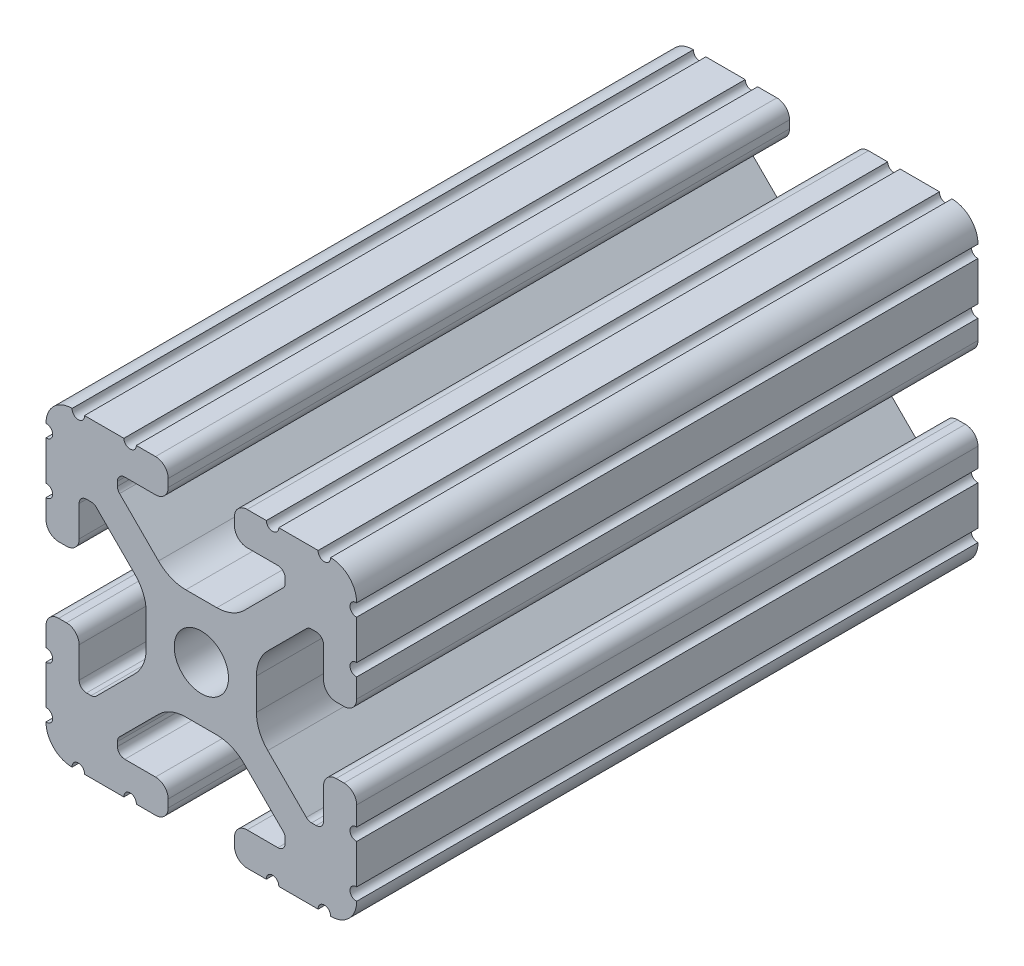
SolidWorks part; units mm, degrees
material "6061 Alloy"
ref_plane "Front Plane" through (0, 0, 0) normal (0, 0, 1) x (1, 0, 0)
ref_plane "Top Plane" through (0, 0, 0) normal (0, 1, 0) x (1, 0, 0)
ref_plane "Right Plane" through (0, 0, 0) normal (1, 0, 0) x (0, 0, -1)
sketch "Sketch1" plane through (0, 0, 0) normal (0, 0, 1) x (1, 0, 0)
  line L0 (0, 25.6181) -> (0, -24.623) construction
  line L1 (-20.8943, 0) -> (20.4607, 0) construction
  line L2 (-10.0229, 12.9148) -> (-5.2522, 8.144)
  line L3 (-10.287, 14.0843) -> (-10.287, 13.5524)
  line L4 (-5.6176, 14.986) -> (-9.3853, 14.986)
  line L5 (-4.064, 17.4964) -> (-4.064, 16.5396)
  line L6 (-7.9742, 19.05) -> (-5.6176, 19.05)
  line L7 (-14.3277, 19.05) -> (-9.4982, 19.05)
  line L8 (-19.05, 9.4961) -> (-19.05, 14.3277)
  line L9 (-19.05, 5.6176) -> (-19.05, 7.9763)
  line L10 (-16.5396, 4.064) -> (-17.4964, 4.064)
  line L11 (-14.986, 9.3853) -> (-14.986, 5.6176)
  line L12 (-13.516, 10.287) -> (-14.0843, 10.287)
  line L13 (-8.1476, 5.2921) -> (-12.8784, 10.0229)
  line L14 (-6.7564, -1.9335) -> (-6.7564, 1.9335)
  line L15 (-12.8784, -10.0229) -> (-8.1476, -5.2921)
  line L16 (-14.0843, -10.287) -> (-13.516, -10.287)
  line L17 (-14.986, -5.6176) -> (-14.986, -9.3853)
  line L18 (-17.4964, -4.064) -> (-16.5396, -4.064)
  line L19 (-19.05, -7.9763) -> (-19.05, -5.6176)
  line L20 (-19.05, -14.3277) -> (-19.05, -9.4961)
  line L21 (-9.4961, -19.05) -> (-14.3277, -19.05)
  line L22 (-5.6176, -19.05) -> (-7.9763, -19.05)
  line L23 (-4.064, -17.4964) -> (-4.064, -16.5396)
  line L24 (10.0229, -12.9148) -> (5.2522, -8.144)
  line L25 (10.287, -14.0843) -> (10.287, -13.5524)
  line L26 (5.6176, -14.986) -> (9.3853, -14.986)
  line L28 (-1.9022, 6.7564) -> (1.9022, 6.7564)
  line L29 (-1.9022, -6.7564) -> (1.9022, -6.7564)
  line L31 (-5.6176, -14.986) -> (-9.3853, -14.986)
  line L32 (-10.287, -14.0843) -> (-10.287, -13.5524)
  line L33 (-10.0229, -12.9148) -> (-5.2522, -8.144)
  line L66 (4.064, -16.5396) -> (4.064, -17.4964)
  line L67 (5.6176, -19.05) -> (7.9763, -19.05)
  line L68 (9.4961, -19.05) -> (14.3277, -19.05)
  line L69 (19.05, -14.3277) -> (19.05, -9.4961)
  line L70 (19.05, -7.9763) -> (19.05, -5.6176)
  line L71 (17.4964, -4.064) -> (16.5396, -4.064)
  line L72 (14.986, -5.6176) -> (14.986, -9.3853)
  line L73 (14.0843, -10.287) -> (13.516, -10.287)
  line L74 (12.8784, -10.0229) -> (8.1476, -5.2921)
  line L75 (6.7564, -1.9335) -> (6.7564, 1.9335)
  line L76 (8.1476, 5.2921) -> (12.8784, 10.0229)
  line L77 (13.516, 10.287) -> (14.0843, 10.287)
  line L78 (14.986, 9.3853) -> (14.986, 5.6176)
  line L79 (16.5396, 4.064) -> (17.4964, 4.064)
  line L80 (19.05, 5.6176) -> (19.05, 7.9763)
  line L81 (19.05, 9.4961) -> (19.05, 14.3277)
  line L82 (14.3277, 19.05) -> (9.4982, 19.05)
  line L83 (7.9742, 19.05) -> (5.6176, 19.05)
  line L84 (4.064, 17.4964) -> (4.064, 16.5396)
  line L85 (5.6176, 14.986) -> (9.3853, 14.986)
  line L86 (10.287, 14.0843) -> (10.287, 13.5524)
  line L87 (10.0229, 12.9148) -> (5.2522, 8.144)
  arc A0 (-10.0229, 12.9148) -> (-10.287, 13.5524) centre (-9.3853, 13.5524) cw
  circle A1 centre (0, 0) radius 3.3274
  arc A2 (-10.287, 14.0843) -> (-9.3853, 14.986) centre (-9.3853, 14.0843) cw
  arc A3 (-4.064, 16.5396) -> (-5.6176, 14.986) centre (-5.6176, 16.5396) cw
  arc A4 (-5.6176, 19.05) -> (-4.064, 17.4964) centre (-5.6176, 17.4964) cw
  arc A5 (-7.9742, 19.05) -> (-9.4982, 19.05) centre (-8.7362, 19.05) cw
  arc A6 (-14.3277, 19.05) -> (-15.8475, 19.05) centre (-15.0876, 18.9933) cw
  arc A7 (-19.05, 15.8475) -> (-15.8475, 19.05) centre (-15.8751, 15.8751) cw
  arc A8 (-19.05, 15.8475) -> (-19.05, 14.3277) centre (-18.9933, 15.0876) cw
  arc A9 (-19.05, 9.4961) -> (-19.05, 7.9763) centre (-18.9933, 8.7362) cw
  arc A10 (-17.4964, 4.064) -> (-19.05, 5.6176) centre (-17.4964, 5.6176) cw
  arc A11 (-14.986, 5.6176) -> (-16.5396, 4.064) centre (-16.5396, 5.6176) cw
  arc A12 (-14.986, 9.3853) -> (-14.0843, 10.287) centre (-14.0843, 9.3853) cw
  arc A13 (-13.516, 10.287) -> (-12.8784, 10.0229) centre (-13.516, 9.3853) cw
  arc A14 (-8.1476, 5.2921) -> (-6.7564, 1.9335) centre (-11.5062, 1.9335) cw
  arc A15 (-6.7564, -1.9335) -> (-8.1476, -5.2921) centre (-11.5062, -1.9335) cw
  arc A16 (-12.8784, -10.0229) -> (-13.516, -10.287) centre (-13.516, -9.3853) cw
  arc A17 (-14.0843, -10.287) -> (-14.986, -9.3853) centre (-14.0843, -9.3853) cw
  arc A18 (-16.5396, -4.064) -> (-14.986, -5.6176) centre (-16.5396, -5.6176) cw
  arc A19 (-19.05, -5.6176) -> (-17.4964, -4.064) centre (-17.4964, -5.6176) cw
  arc A20 (-19.05, -7.9763) -> (-19.05, -9.4961) centre (-18.9933, -8.7362) cw
  arc A21 (-19.05, -14.3277) -> (-19.05, -15.8475) centre (-18.9933, -15.0876) cw
  arc A22 (-15.8475, -19.05) -> (-19.05, -15.8475) centre (-15.8751, -15.8751) cw
  arc A23 (-15.8475, -19.05) -> (-14.3277, -19.05) centre (-15.0876, -18.9933) cw
  arc A24 (-9.4961, -19.05) -> (-7.9763, -19.05) centre (-8.7362, -18.9933) cw
  arc A25 (-4.064, -17.4964) -> (-5.6176, -19.05) centre (-5.6176, -17.4964) cw
  arc A26 (-5.2522, -8.144) -> (-1.9022, -6.7564) centre (-1.9022, -11.494) cw
  arc A27 (1.9022, -6.7564) -> (5.2522, -8.144) centre (1.9022, -11.494) cw
  arc A28 (10.0229, -12.9148) -> (10.287, -13.5524) centre (9.3853, -13.5524) cw
  arc A29 (10.287, -14.0843) -> (9.3853, -14.986) centre (9.3853, -14.0843) cw
  arc A30 (4.064, -16.5396) -> (5.6176, -14.986) centre (5.6176, -16.5396) cw
  arc A31 (-4.064, -16.5396) -> (-5.6176, -14.986) centre (-5.6176, -16.5396) ccw
  arc A32 (-10.287, -14.0843) -> (-9.3853, -14.986) centre (-9.3853, -14.0843) ccw
  arc A33 (-10.0229, -12.9148) -> (-10.287, -13.5524) centre (-9.3853, -13.5524) ccw
  arc A79 (4.064, -17.4964) -> (5.6176, -19.05) centre (5.6176, -17.4964) ccw
  arc A80 (9.4961, -19.05) -> (7.9763, -19.05) centre (8.7362, -18.9933) ccw
  arc A81 (15.8475, -19.05) -> (14.3277, -19.05) centre (15.0876, -18.9933) ccw
  arc A82 (15.8475, -19.05) -> (19.05, -15.8475) centre (15.8751, -15.8751) ccw
  arc A83 (19.05, -14.3277) -> (19.05, -15.8475) centre (18.9933, -15.0876) ccw
  arc A84 (19.05, -7.9763) -> (19.05, -9.4961) centre (18.9933, -8.7362) ccw
  arc A85 (19.05, -5.6176) -> (17.4964, -4.064) centre (17.4964, -5.6176) ccw
  arc A86 (16.5396, -4.064) -> (14.986, -5.6176) centre (16.5396, -5.6176) ccw
  arc A87 (14.0843, -10.287) -> (14.986, -9.3853) centre (14.0843, -9.3853) ccw
  arc A88 (12.8784, -10.0229) -> (13.516, -10.287) centre (13.516, -9.3853) ccw
  arc A89 (6.7564, -1.9335) -> (8.1476, -5.2921) centre (11.5062, -1.9335) ccw
  arc A90 (8.1476, 5.2921) -> (6.7564, 1.9335) centre (11.5062, 1.9335) ccw
  arc A91 (13.516, 10.287) -> (12.8784, 10.0229) centre (13.516, 9.3853) ccw
  arc A92 (14.986, 9.3853) -> (14.0843, 10.287) centre (14.0843, 9.3853) ccw
  arc A93 (14.986, 5.6176) -> (16.5396, 4.064) centre (16.5396, 5.6176) ccw
  arc A94 (17.4964, 4.064) -> (19.05, 5.6176) centre (17.4964, 5.6176) ccw
  arc A95 (19.05, 9.4961) -> (19.05, 7.9763) centre (18.9933, 8.7362) ccw
  arc A96 (19.05, 15.8475) -> (19.05, 14.3277) centre (18.9933, 15.0876) ccw
  arc A97 (19.05, 15.8475) -> (15.8475, 19.05) centre (15.8751, 15.8751) ccw
  arc A98 (14.3277, 19.05) -> (15.8475, 19.05) centre (15.0876, 18.9933) ccw
  arc A99 (7.9742, 19.05) -> (9.4982, 19.05) centre (8.7362, 19.05) ccw
  arc A100 (5.6176, 19.05) -> (4.064, 17.4964) centre (5.6176, 17.4964) ccw
  arc A101 (4.064, 16.5396) -> (5.6176, 14.986) centre (5.6176, 16.5396) ccw
  arc A102 (10.287, 14.0843) -> (9.3853, 14.986) centre (9.3853, 14.0843) ccw
  arc A103 (10.0229, 12.9148) -> (10.287, 13.5524) centre (9.3853, 13.5524) ccw
  arc A104 (1.9022, 6.7564) -> (5.2522, 8.144) centre (1.9022, 11.494) ccw
  arc A105 (-5.2522, 8.144) -> (-1.9022, 6.7564) centre (-1.9022, 11.494) ccw
  dimension "D1" = 6.6548
  dimension "D2" = 19.05
  dimension "D3" = 38.1
  dimension "D4" = 20.574
  dimension "D5" = 13.5128
  dimension "D6" = 4.064
  dimension "D7" = 8.128
  dimension "D8" = 4.064
  dimension "D9" = 12.2936
extrude "Extrude1" add sketch "Sketch1" against normal blind 76.2
